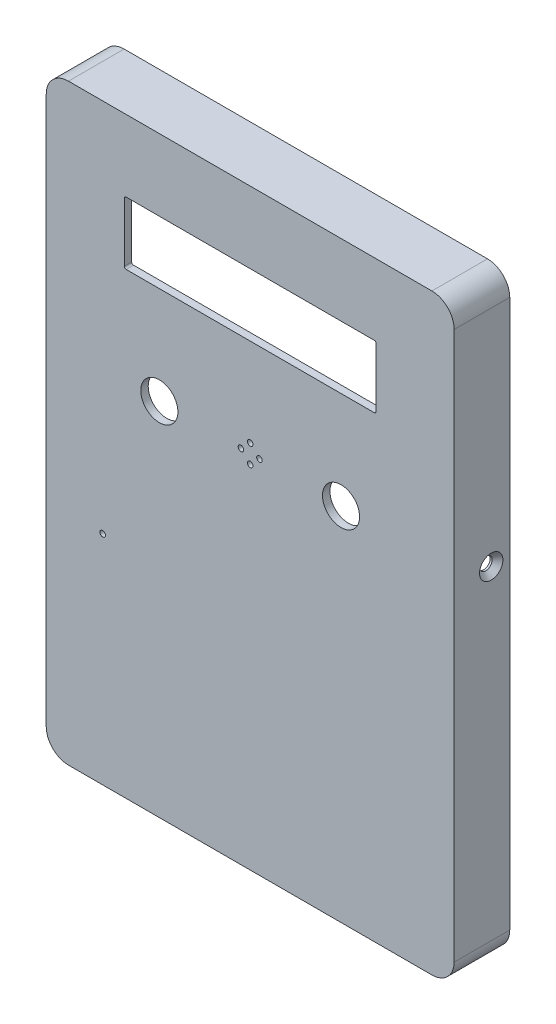
SolidWorks part; units mm, degrees
ref_plane "Front Plane" through (0, 0, 0) normal (0, 0, 1) x (1, 0, 0)
ref_plane "Top Plane" through (0, 0, 0) normal (0, 1, 0) x (1, 0, 0)
ref_plane "Right Plane" through (0, 0, 0) normal (1, 0, 0) x (0, 0, -1)
sketch "Sketch1" plane through (0, 0, 0) normal (0, 0, 1) x (1, 0, 0)
  line L0 (-53, 60.375) -> (-53, -87.375) construction
  line L1 (-50, 61.375) -> (50, 61.375) construction
  line L2 (-50, 61.375) -> (-50, -61.375) construction
  line L3 (-50, -61.375) -> (50, -61.375) construction
  line L4 (50, 61.375) -> (50, -61.375) construction
  line L5 (-50, 61.375) -> (50, -61.375) construction
  line L6 (-50, -61.375) -> (50, 61.375) construction
  line L7 (-49, -91.375) -> (49, -91.375) construction
  line L8 (53, 60.375) -> (53, -87.375) construction
  line L9 (-49, 64.375) -> (49, 64.375) construction
  line L14 (-49, 66.375) -> (49, 66.375)
  line L15 (55, 60.375) -> (55, -87.375)
  line L16 (-49, -93.375) -> (49, -93.375)
  line L17 (-55, 60.375) -> (-55, -87.375)
  arc A8 (53, 60.375) -> (49, 64.375) centre (49, 60.375) ccw construction
  arc A9 (-49, -91.375) -> (-53, -87.375) centre (-49, -87.375) cw construction
  arc A10 (49, -91.375) -> (53, -87.375) centre (49, -87.375) ccw construction
  arc A11 (-49, 64.375) -> (-53, 60.375) centre (-49, 60.375) ccw construction
  arc A12 (-55, 60.375) -> (-49, 66.375) centre (-49, 60.375) cw
  arc A13 (55, 60.375) -> (49, 66.375) centre (49, 60.375) ccw
  arc A14 (49, -93.375) -> (55, -87.375) centre (49, -87.375) ccw
  arc A15 (-49, -93.375) -> (-55, -87.375) centre (-49, -87.375) cw
  point P0 (0, 0)
  dimension "D4" = 6
  dimension "D12" = 4
  dimension "D13" = 4
  dimension "D1" = 100
  dimension "D2" = 122.75
  dimension "D3" = 3
  dimension "D5" = 2
  dimension "D6" = 3
  dimension "D7" = 2
  dimension "D8" = 3
  dimension "D9" = 2
  dimension "D10" = 30
  dimension "D11" = 2
extrude "Boss-Extrude1" add sketch "Sketch1" along normal blind 15
shell "Shell1" thickness 2
sketch "Sketch3" plane through (0, 0, 15) normal (0, 0, 1) x (1, 0, 0)
  line L0 (-24.5, 3.875) -> (24.5, 3.875) construction
  line L1 (-50, 61.375) -> (50, 61.375) construction
  line L2 (0, 0) -> (0, 3.875) construction
  line L4 (-34.45, 47.575) -> (34.45, 47.575) construction
  line L5 (-34.45, 47.575) -> (-34.45, 29.675) construction
  line L6 (-34.45, 29.675) -> (34.45, 29.675) construction
  line L7 (34.45, 47.575) -> (34.45, 29.675) construction
  line L8 (-34.45, 47.575) -> (34.45, 29.675) construction
  line L9 (-34.45, 29.675) -> (34.45, 47.575) construction
  line L11 (-50, 61.375) -> (-50, -61.375) construction
  line L12 (-33.45, 47.075) -> (33.45, 47.075)
  line L13 (33.95, 46.575) -> (33.95, 30.675)
  line L14 (-33.45, 30.175) -> (33.45, 30.175)
  line L15 (-33.95, 46.575) -> (-33.95, 30.675)
  line L16 (-33.95, 47.075) -> (33.95, 47.075) construction
  line L17 (33.95, 47.075) -> (33.95, 30.175) construction
  line L18 (-33.95, 30.175) -> (33.95, 30.175) construction
  line L19 (-33.95, 47.075) -> (-33.95, 30.175) construction
  circle A0 centre (-24.5, 3.875) radius 5
  circle A1 centre (24.5, 3.875) radius 5
  arc A2 (33.45, 47.075) -> (33.95, 46.575) centre (33.45, 46.575) cw
  arc A3 (33.95, 30.675) -> (33.45, 30.175) centre (33.45, 30.675) cw
  arc A4 (-33.45, 30.175) -> (-33.95, 30.675) centre (-33.45, 30.675) cw
  arc A5 (-33.45, 47.075) -> (-33.95, 46.575) centre (-33.45, 46.575) ccw
  point P10 (0, 38.625)
  dimension "D1" = 49
  dimension "D3" = 10
  dimension "D9" = 0.5
  dimension "D2" = 57.5
  dimension "D4" = 15.55
  dimension "D5" = 13.8
  dimension "D6" = 17.9
  dimension "D7" = 68.9
  dimension "D8" = 1
extrude "Cut-Extrude1" cut sketch "Sketch3" against normal through all
ref_plane "Plane1" through (0, 0, 7) normal (0, 0, -1) x (-1, 0, 0)
sketch "Sketch4" plane through (0, 0, 7) normal (0, 0, -1) x (-1, 0, 0)
  line L0 (50, 61.375) -> (-50, 61.375) construction
  line L1 (-50, 61.375) -> (-50, -61.375) construction
  line L2 (50, 61.375) -> (50, -61.375) construction
  line L3 (50, -61.375) -> (-50, -61.375) construction
  circle A0 centre (-45, 56.375) radius 3
  circle A1 centre (-45, -56.375) radius 3
  circle A2 centre (45, 56.375) radius 3
  circle A3 centre (45, -56.375) radius 3
  dimension "D2" = 5
  dimension "D3" = 6
  dimension "D5" = 5
  dimension "D6" = 5
  dimension "D7" = 5
  dimension "D8" = 5
  dimension "D9" = 5
  dimension "D1" = 5
  dimension "D4" = 5
extrude "Boss-Extrude2" add sketch "Sketch4" against normal up to next draft 1 draft outward yes
hole_wizard "M3 Tapped Hole1" positions "Sketch5" profile "Sketch6" tap size "M3" standard "ISO"
sketch "Sketch5" plane through (0, 0, 7) normal (0, 0, -1) x (-1, 0, 0)
  point P0 (-45, 56.375)
  point P3 (45, 56.375)
  point P6 (45, -56.375)
  point P9 (-45, -56.375)
sketch "Sketch6" plane through (45, 56.375, 7) normal (1, 0, 0) x (0, 1, 0)
  line L0 (0, 0) -> (0, 6.7511)
  line L1 (0, 6.7511) -> (1.25, 6)
  line L2 (1.25, 6) -> (1.25, 0.5)
  line L3 (1.25, 0.5) -> (1.75, 0)
  line L5 (1.75, 0) -> (0, 0)
  line L6 (-1.25, 0.5) -> (-1.75, 0) construction
  line L10 (0, 6.7511) -> (-1.25, 6) construction
  line L11 (0, -6.35) -> (0, 107.95) construction
  dimension "Tap Drill Dia." = 2.5
  dimension "Tap Drill Depth" = 6
  dimension "Near C'Sink Dia." = 3.5
  dimension "Near C'Sink Angle" = 90
  dimension "Drill Angle" = 118
cosmetic thread "Hole Thread1" parameters "D1"=5, "D2"=3
cosmetic thread "Hole Thread2" parameters "D1"=5, "D2"=3
cosmetic thread "Hole Thread3" parameters "D1"=5, "D2"=3
cosmetic thread "Hole Thread4" parameters "D1"=5, "D2"=3
ref_plane "Plane2" through (0, 0, -5) normal (0, 0, -1) x (-1, 0, 0)
sketch "Sketch9" plane through (0, 0, -5) normal (0, 0, -1) x (-1, 0, 0)
  line L0 (49, 64.375) -> (-49, 64.375) construction
  line L1 (-53, 60.375) -> (-53, -87.375) construction
  line L3 (49, -91.375) -> (-49, -91.375) construction
  line L4 (53, 60.375) -> (53, -87.375) construction
  circle A0 centre (-47, 58.375) radius 3
  circle A1 centre (47, 58.375) radius 3
  circle A2 centre (-47, -85.375) radius 3
  circle A3 centre (47, -85.375) radius 3
  dimension "D1" = 6
  dimension "D3" = 6
  dimension "D4" = 6
  dimension "D5" = 6
  dimension "D2" = 6
sketch "Sketch14" plane through (0, 0, 15) normal (0, 0, 1) x (1, 0, 0)
  line L0 (-19.5, 3.875) -> (19.5, 3.875) construction
  line L1 (0, 6.375) -> (0, 1.375) construction
  circle A0 centre (-24.5, 3.875) radius 5 construction
  circle A1 centre (24.5, 3.875) radius 5 construction
  circle A2 centre (0, 6.375) radius 0.75
  circle A3 centre (0, 1.375) radius 0.75
  circle A4 centre (2.5, 3.875) radius 0.75
  circle A5 centre (-2.5, 3.875) radius 0.75
  dimension "D1" = 1.5
  dimension "D2" = 5
  dimension "D3" = 5
extrude "Cut-Extrude3" cut sketch "Sketch14" against normal blind 10
hole_wizard "CSK for M3 Countersunk Flat Head Screw1" positions "Sketch16" profile "Sketch17" countersink size "M3" standard "ISO" end condition up to next
sketch "Sketch16" plane through (-55, 0, 0) normal (-1, 0, 0) x (0, 0, 1)
  line L0 (15, 60.375) -> (15, -87.375) construction
  point P0 (5, 0)
  dimension "D1" = 10
sketch "Sketch17" plane through (-55, 0, 5) normal (0, 1, 0) x (0, 0, 1)
  line L0 (0, 0) -> (0, 2)
  line L1 (0, 2) -> (1.7, 2)
  line L2 (1.7, 2) -> (1.7, 1.45)
  line L3 (1.7, 1.45) -> (3.15, 0)
  line L5 (3.15, 0) -> (0, 0)
  line L6 (-1.7, 1.45) -> (-3.15, 0) construction
  line L11 (0, -6.35) -> (0, 107.95) construction
  dimension "Thru Hole Dia." = 3.4
  dimension "Thru Hole Depth" = 2
  dimension "Near C'Sink Dia." = 6.3
  dimension "Near C'Sink Angle" = 90
hole_wizard "CSK SLOT for M3 Countersunk Flat Head Screw1" positions "Sketch18" profile "Sketch19" size "M3" standard "ISO" slot yes end condition up to next
sketch "Sketch18" plane through (55, 0, 0) normal (1, 0, 0) x (0, 0, -1)
  line L0 (-15, -87.375) -> (-15, 60.375) construction
  point P0 (-5, 0)
  dimension "D1" = 10
sketch "Sketch19" plane through (55, 0, 5) normal (0, 1, 0) x (0, 0, -1)
  line L0 (0, 0) -> (0, 2)
  line L1 (0, 2) -> (1.7, 2)
  line L2 (1.7, 2) -> (1.7, 1.45)
  line L3 (1.7, 1.45) -> (3.15, 0)
  line L5 (3.15, 0) -> (0, 0)
  line L6 (-1.7, 1.45) -> (-3.15, 0) construction
  line L11 (0, -6.35) -> (0, 107.95) construction
  dimension "Thru Hole Dia." = 3.4
  dimension "Thru Hole Depth" = 2
  dimension "Near C'Sink Dia." = 6.3
  dimension "Near C'Sink Angle" = 90
sketch "Sketch20" plane through (0, 0, 15) normal (0, 0, 1) x (1, 0, 0)
  line L0 (-50, 61.375) -> (-50, -61.375) construction
  line L1 (-50, -61.375) -> (50, -61.375) construction
  circle A0 centre (-39.79, -34.725) radius 0.75
  dimension "D2" = 26.65
  dimension "D3" = 1.5
  dimension "D1" = 10.21
extrude "Cut-Extrude4" cut sketch "Sketch20" against normal blind 10
